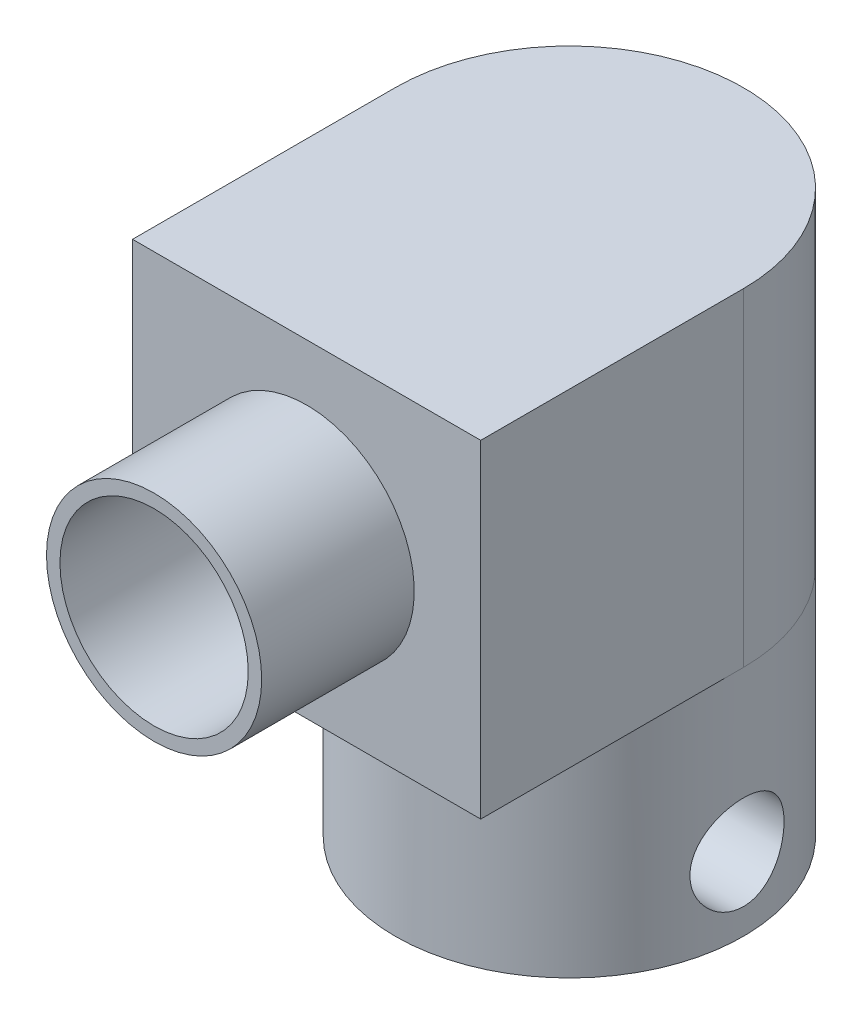
SolidWorks part; units mm, degrees
material "AISI 316 Annealed Stainless Steel Bar (SS)"
ref_plane "Front Plane" through (0, 0, 0) normal (0, 0, 1) x (1, 0, 0)
ref_plane "Top Plane" through (0, 0, 0) normal (0, 1, 0) x (1, 0, 0)
ref_plane "Right Plane" through (0, 0, 0) normal (1, 0, 0) x (0, 0, -1)
sketch "Sketch1" plane through (0, 0, 0) normal (0, 1, 0) x (1, 0, 0)
  circle A0 centre (0, 0) radius 20.55
  dimension "D1" = 41.1
extrude "BASE" add sketch "Sketch1" along normal blind 27.4955
sketch "Sketch2" plane through (0, 27.4955, 0) normal (0, 1, 0) x (1, 0, 0)
  line L0 (-20.55, 0) -> (-20.55, -31.012)
  line L1 (-20.55, -31.012) -> (20.55, -31.012)
  line L2 (20.55, -31.012) -> (20.55, 0)
  circle A0 centre (0, 0) radius 20.55 construction
  circle A1 centre (0, 0) radius 20.55
  arc A2 (20.55, 0) -> (-20.55, 0) centre (0, 0) ccw
  point P2 (0, 20.55)
  point P10 (0, -20.55)
  dimension "D2" = 51.562
  dimension "D1" = 0
extrude "TOP" add sketch "Sketch2" along normal blind 38.7223
sketch "Sketch3" plane through (0, 0, 0) normal (0, -1, 0) x (1, 0, 0)
  line L0 (0, 0) -> (50000, 0) construction
  line L1 (0, 0) -> (0, 50000) construction
  line L2 (0, 0) -> (11.2, 11.2) construction
  circle A0 centre (11.2, 11.2) radius 2
  circle A1 centre (-11.2, -11.2) radius 2
  point P12 (0, 0)
  dimension "D1" = 4
  dimension "D2" = 22.4
  dimension "D3" = 45
  dimension "D4" = 2
extrude "MOUNTING" cut sketch "Sketch3" against normal blind 6.35
sketch "Sketch4" plane through (0, 0, 0) normal (1, 0, 0) x (0, 0, -1)
  line L0 (-20.55, 0) -> (20.55, 0) construction
  circle A0 centre (0, 8.6) radius 5.5562
  dimension "D2" = 11.1125
  dimension "D1" = 8.6
extrude "NPTF" cut sketch "Sketch4" against normal through all both and the other way through all
sketch "Sketch5" plane through (0, 0, 31.012) normal (0, 0, 1) x (1, 0, 0)
  line L0 (0, 27.4955) -> (0, 66.2178) construction
  line L1 (-20.55, 27.4955) -> (20.55, 27.4955) construction
  line L2 (-20.55, 66.2178) -> (20.55, 66.2178) construction
  circle A0 centre (0, 46.8567) radius 12.7
  circle A1 centre (0, 46.8567) radius 11.1125
  point P8 (0, 0)
  dimension "D1" = 25.4
  dimension "D2" = 1.5875
extrude "CABLE_TUBE" add sketch "Sketch5" along normal blind 18.0086
ref_plane "TOP_REF" through (0, 27.4955, 0) normal (0, -1, 0) x (-1, 0, 0)
split line "TOP_SPLIT"
